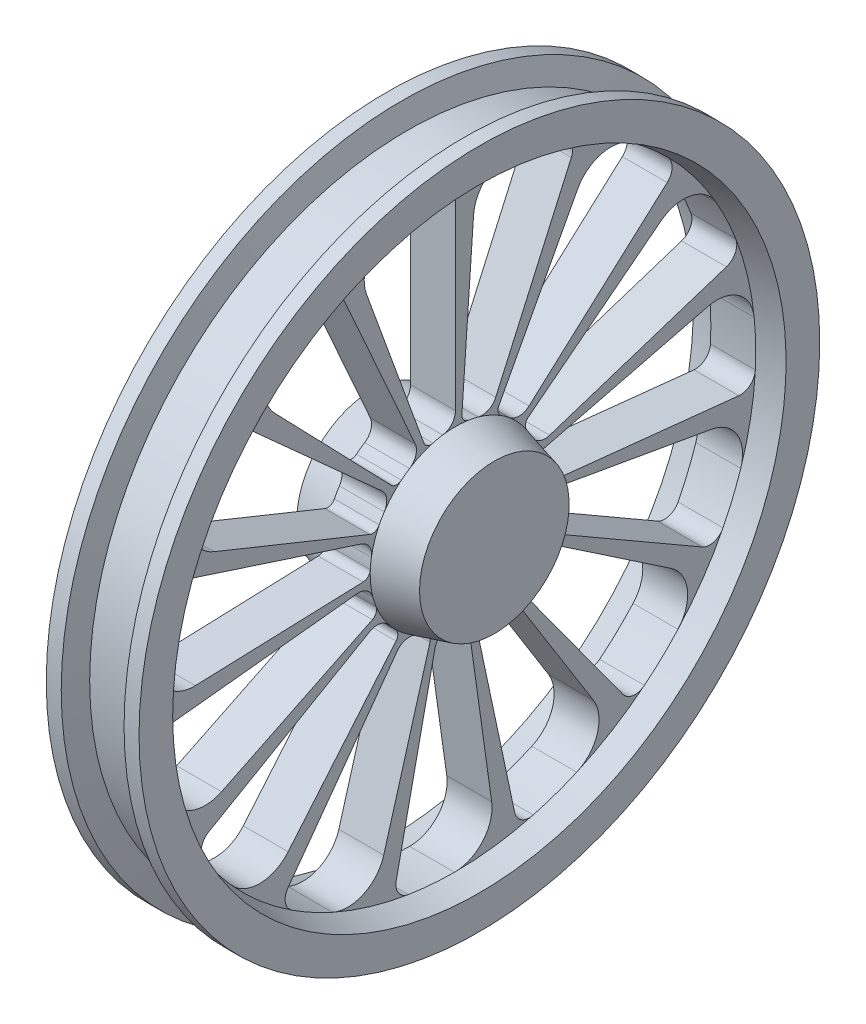
SolidWorks part; units mm, degrees
material "Alliage 1060"
ref_plane "Plan de face" through (0, 0, 0) normal (0, 0, 1) x (1, 0, 0)
ref_plane "Plan de dessus" through (0, 0, 0) normal (0, 1, 0) x (1, 0, 0)
ref_plane "Plan de droite" through (0, 0, 0) normal (1, 0, 0) x (0, 0, -1)
sketch "Esquisse1" plane through (0, 0, 0) normal (0, 0, 1) x (1, 0, 0)
  line L0 (0, 0) -> (0, 300.8113) construction
  line L1 (0, 0) -> (-82, 0) construction
  line L2 (-82, 0) -> (-82, 100)
  line L3 (-82, 100) -> (-30, 113.9334)
  line L4 (-30, 113.9334) -> (-30, 401.4256)
  line L5 (-30, 401.4256) -> (-62, 410)
  line L6 (-62, 410) -> (-62, 455)
  line L7 (-62, 455) -> (-42, 455)
  line L8 (-42, 455) -> (-33.9615, 425)
  line L9 (-33.9615, 425) -> (33.9615, 425)
  line L10 (82, 0) -> (82, 100)
  line L11 (82, 100) -> (30, 113.9334)
  line L12 (30, 113.9334) -> (30, 401.4256)
  line L13 (30, 401.4256) -> (62, 410)
  line L14 (62, 410) -> (62, 455)
  line L15 (62, 455) -> (42, 455)
  line L16 (42, 455) -> (33.9615, 425)
  line L17 (-82, 0) -> (82, 0)
  point P3 (0, 300.8113)
  point P13 (-31.3936, 135.2283)
  point P22 (0, 425)
  dimension "D1" = 164
  dimension "D2" = 124
  dimension "D3" = 45
  dimension "D4" = 30
  dimension "D5" = 20
  dimension "15" = 15
  dimension "D6" = 15
  dimension "D7" = 910
  dimension "D8" = 60
  dimension "D9" = 200
  dimension "D10" = 15
revolve "Révolution1" add sketch "Esquisse1" angle 360 about L17
sketch "Esquisse2" plane through (-30, 0, 0) normal (-1, 0, 0) x (0, 0, 1)
  line L0 (0, 132.4317) -> (0, 380.9009)
  line L1 (42.2495, 116.0795) -> (118.9719, 326.8725)
  line L2 (0, 0) -> (213.4203, 586.3674) construction
  circle A0 centre (0, 0) radius 113.9334 construction
  arc A1 (30.2017, 109.8575) -> (17.0134, 112.6559) centre (0, 0) ccw
  circle A2 centre (0, 0) radius 401.4256 construction
  arc A3 (82.2294, 392.9133) -> (21.0487, 400.8734) centre (0, 0) ccw
  arc A4 (0, 132.4317) -> (17.0134, 112.6559) centre (20, 132.4317) ccw
  arc A5 (21.0487, 400.8734) -> (0, 380.9009) centre (20, 380.9009) ccw
  arc A6 (118.9719, 326.8725) -> (82.2294, 392.9133) centre (71.9872, 343.9736) ccw
  arc A7 (42.2495, 116.0795) -> (30.2017, 109.8575) centre (32.8526, 119.4997) cw
  dimension "D2" = 20
  dimension "D3" = 20
  dimension "D4" = 50
  dimension "D5" = 10
  dimension "D1" = 20
extrude "Enlèv. mat.-Extru.1" cut sketch "Esquisse2" against normal through all contours A3 A5 L0 A4 A1 A7 L1 A6
pattern_circular "Répétition circulaire1" count 15 every 24 about axis through (0, 0, 0) along (1, 0, 0) of "Enlèv. mat.-Extru.1"
equation "\"A\"= 124"
equation "\"B\"= 910"
equation "\"D1@Esquisse1\"=\"A\"+40"
equation "\"D2@Esquisse1\"=\"A\""
equation "\"D7@Esquisse1\"=\"B\""
